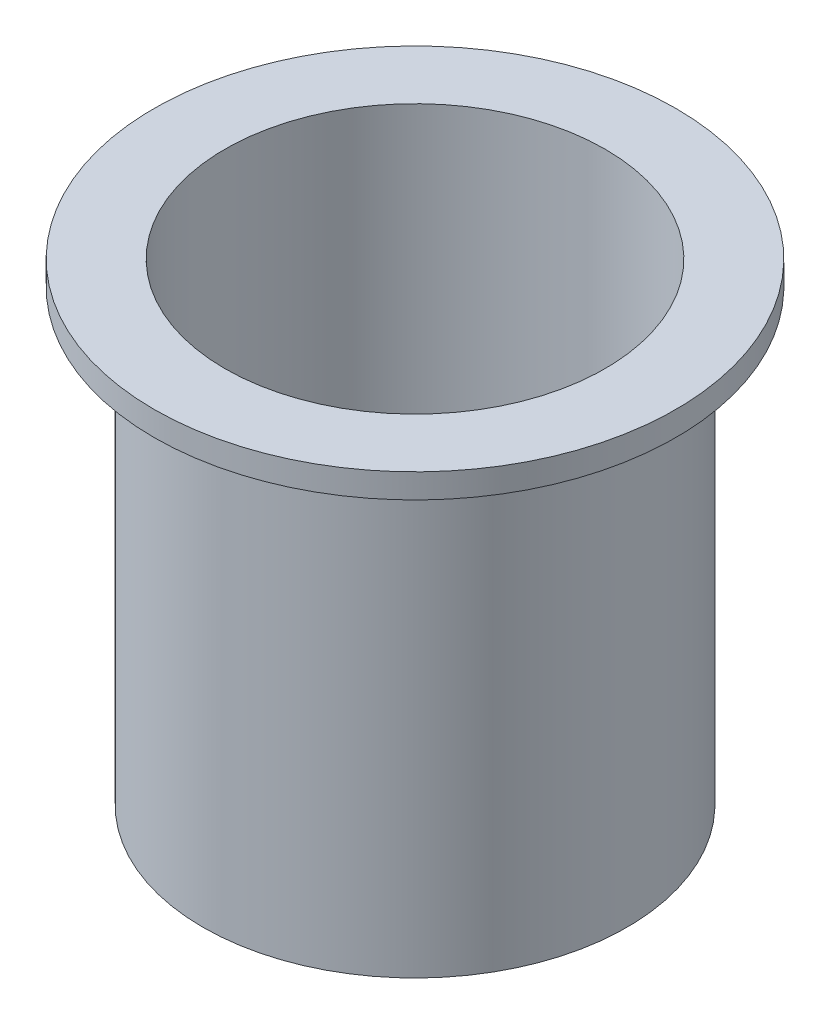
SolidWorks part; units mm, degrees
ref_plane "Front Plane" through (0, 0, 0) normal (0, 0, 1) x (1, 0, 0)
ref_plane "Top Plane" through (0, 0, 0) normal (0, 1, 0) x (1, 0, 0)
ref_plane "Right Plane" through (0, 0, 0) normal (1, 0, 0) x (0, 0, -1)
sketch "Sketch1" plane through (0, 0, 0) normal (0, 1, 0) x (1, 0, 0)
  circle A0 centre (0, 0) radius 43.5
  circle A1 centre (0, 0) radius 38.5
  dimension "D1" = 87
  dimension "D2" = 77
extrude "Boss-Extrude3" add sketch "Sketch1" along normal blind 95
sketch "Sketch3" plane through (0, 95, 0) normal (0, 1, 0) x (1, 0, 0)
  circle A0 centre (0, 0) radius 53.5
  dimension "D1" = 107
extrude "Boss-Extrude4" add sketch "Sketch3" along normal blind 5
sketch "Sketch4" plane through (0, 95, 0) normal (0, -1, 0) x (1, 0, 0)
  circle A0 centre (0, 0) radius 38.5
extrude "Cut-Extrude1" cut sketch "Sketch4" against normal blind 5
sketch "Sketch5" plane through (0, 100, 0) normal (0, 1, 0) x (1, 0, 0)
  circle A0 centre (0, 0) radius 39
  dimension "D1" = 78
extrude "Cut-Extrude2" cut sketch "Sketch5" against normal blind 120
sketch "Sketch6" plane through (0, 0, 0) normal (0, -1, 0) x (1, 0, 0)
  circle A0 centre (0, 0) radius 43.5
extrude "Cut-Extrude3" cut sketch "Sketch6" against normal blind 3
